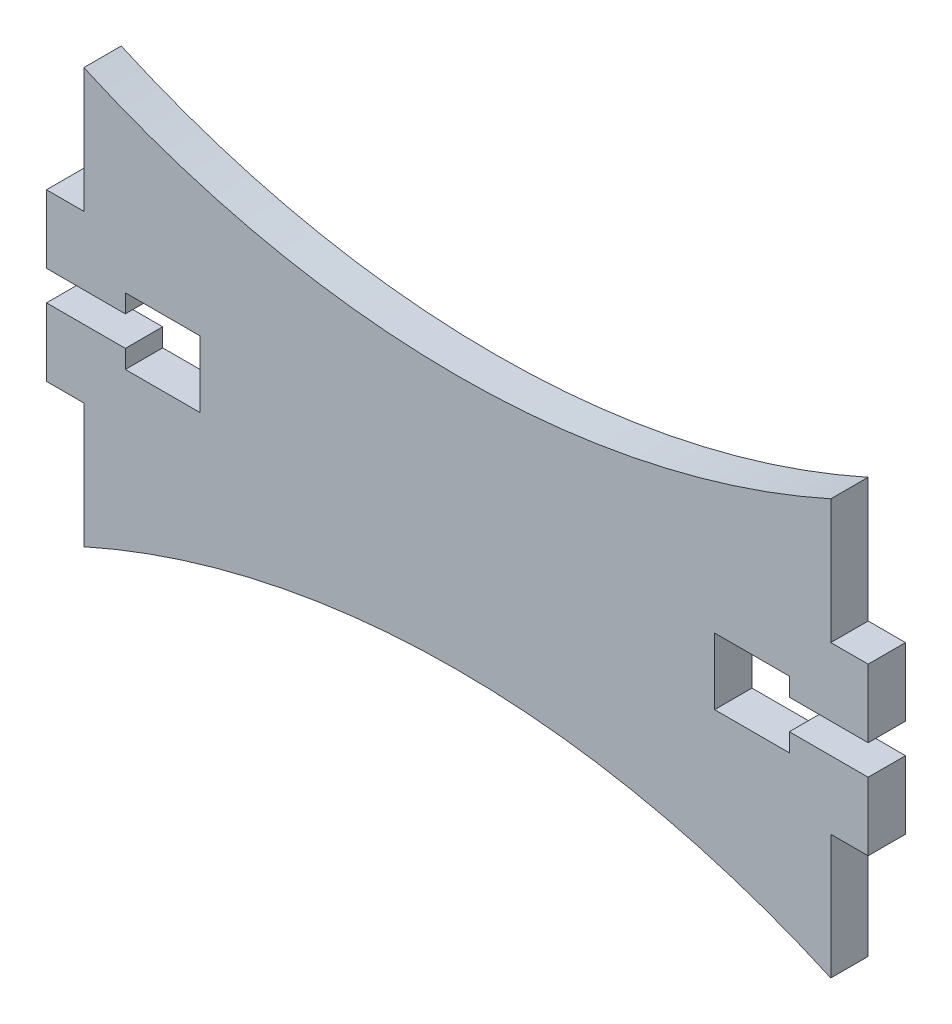
SolidWorks part; units mm, degrees
material "Oak"
ref_plane "Front Plane" through (0, 0, 0) normal (0, 0, 1) x (1, 0, 0)
ref_plane "Top Plane" through (0, 0, 0) normal (0, 1, 0) x (1, 0, 0)
ref_plane "Right Plane" through (0, 0, 0) normal (1, 0, 0) x (0, 0, -1)
sketch "Sketch1" plane through (0, 0, 0) normal (0, 0, 1) x (1, 0, 0)
  line L1 (-49.5, -10) -> (49.5, -10)
  line L2 (-49.5, -10) -> (-49.5, 10)
  line L3 (-49.5, 10) -> (49.5, 10)
  line L4 (49.5, -10) -> (49.5, 10)
  line L5 (-49.5, -10) -> (49.5, 10) construction
  line L6 (-49.5, 10) -> (49.5, -10) construction
  line L7 (-45, -25) -> (45, -25)
  line L8 (-45, -25) -> (-45, 25)
  line L9 (-45, 25) -> (45, 25)
  line L10 (45, -25) -> (45, 25)
  line L11 (-45, -25) -> (45, 25) construction
  line L12 (-45, 25) -> (45, -25) construction
  line L13 (-49.5, -1.8) -> (49.5, -1.8)
  line L14 (-49.5, -1.8) -> (-49.5, 1.8)
  line L15 (-49.5, 1.8) -> (49.5, 1.8)
  line L16 (49.5, -1.8) -> (49.5, 1.8)
  line L17 (-49.5, -1.8) -> (49.5, 1.8) construction
  line L18 (-49.5, 1.8) -> (49.5, -1.8) construction
  line L19 (-35.5, -1.8) -> (35.5, -1.8)
  line L20 (-35.5, -1.8) -> (-35.5, 1.8)
  line L21 (-35.5, 1.8) -> (35.5, 1.8)
  line L22 (35.5, -1.8) -> (35.5, 1.8)
  line L23 (-35.5, -1.8) -> (35.5, 1.8) construction
  line L24 (-35.5, 1.8) -> (35.5, -1.8) construction
  line L25 (31, -4) -> (40, -4)
  line L26 (31, -4) -> (31, 4)
  line L27 (31, 4) -> (40, 4)
  line L28 (40, -4) -> (40, 4)
  line L29 (31, -4) -> (40, 4) construction
  line L30 (31, 4) -> (40, -4) construction
  line L31 (-31, -4) -> (-40, -4)
  line L32 (-31, -4) -> (-31, 4)
  line L33 (-31, 4) -> (-40, 4)
  line L34 (-40, -4) -> (-40, 4)
  line L35 (-31, -4) -> (-40, 4) construction
  line L36 (-31, 4) -> (-40, -4) construction
  arc A0 (-45, 25) -> (45, 25) centre (0, 125) ccw
  arc A1 (-45, -25) -> (45, -25) centre (0, -125) cw
  point P0 (0, 0)
  point P4 (0, 0)
  point P7 (0, 0)
  point P18 (0, 0)
  point P23 (35.5, 0)
  point P28 (-35.5, 0)
  dimension "D5" = 100
  dimension "D6" = 100
  dimension "D1" = 20
  dimension "D2" = 99
  dimension "D3" = 4.5
  dimension "D4" = 15
  dimension "D7" = 9
  dimension "D8" = 3.6
  dimension "D9" = 14
  dimension "D10" = 8
  dimension "D11" = 9
  dimension "D12" = 8
extrude "Boss-Extrude1" add sketch "Sketch1" along normal blind 4.5 contours A0 L8 L3 L10 | L15 L34 L33 L32 L21 L26 L27 L28 L10 L3 L8 | L32 L19 L26 L21 | L31 L34 L13 L8 L1 L10 L28 L25 L26 L19 L32 | L8 A1 L10 L1 | L13 L2 L1 L8 | L2 L15 L8 L3 | L10 L15 L4 L3 | L13 L10 L1 L4 | L9
